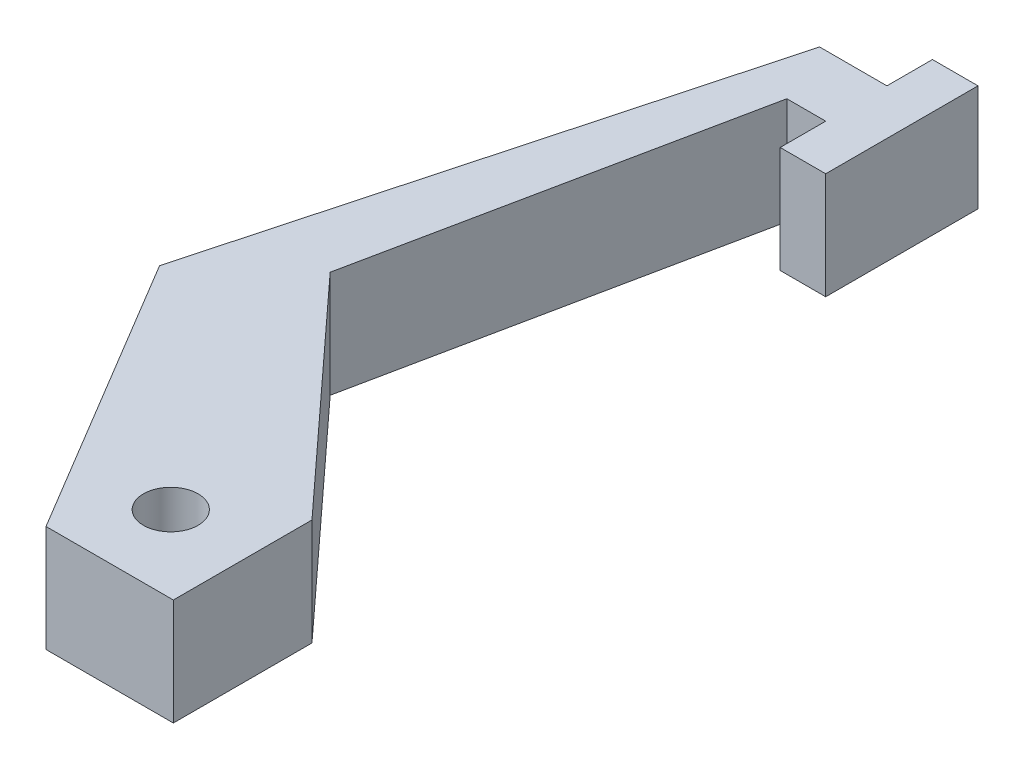
SolidWorks part; units mm, degrees
ref_plane "Front Plane" through (0, 0, 0) normal (0, 0, 1) x (1, 0, 0)
ref_plane "Top Plane" through (0, 0, 0) normal (0, 1, 0) x (1, 0, 0)
ref_plane "Right Plane" through (0, 0, 0) normal (1, 0, 0) x (0, 0, -1)
sketch "Sketch1" plane through (0, 0, 0) normal (0, 1, 0) x (1, 0, 0)
  line L13 (0, 0) -> (-13.9808, 0)
  line L14 (0, 0) -> (0, 15.2189)
  line L15 (0, 15.2189) -> (-22.5542, 39.772)
  line L16 (-22.5542, 39.772) -> (-13.9808, 81.3354)
  line L17 (-13.9808, 81.3354) -> (-9.7151, 81.3354)
  line L18 (-9.7151, 81.3354) -> (-9.7151, 76.3354)
  line L19 (-9.7151, 76.3354) -> (-4.7151, 76.3354)
  line L20 (-4.7151, 76.3354) -> (-4.7151, 93.0551)
  line L21 (-4.7151, 93.0551) -> (-9.7151, 93.0551)
  line L22 (-9.7151, 93.0551) -> (-9.7151, 88.0551)
  line L23 (-9.7151, 88.0551) -> (-17.1058, 88.0551)
  line L24 (-17.1058, 88.0551) -> (-32.5429, 31.0284)
  line L25 (-32.5429, 31.0284) -> (-13.9808, 0)
  circle A0 centre (-8.7368, 8.4549) radius 3
  point P12 (0, 0)
  point P14 (0, 0)
  point P15 (-8.7368, 8.4549)
  point P16 (0, 15.2189)
  point P17 (-13.9808, 0)
  point P18 (-30.8436, 47.8887)
  point P19 (-38.5545, 39.772)
  point P20 (-14.0801, 100.102)
  point P21 (-17.0875, 112.1316)
  point P22 (0, 0)
  point P23 (0, 0)
  point P24 (0, 0)
  point P27 (-27.7805, 44.9665)
  point P28 (-9.7151, 90.5551)
  point P29 (0, 0)
  point P31 (-15.4712, 85.5125)
  point P32 (-22.5542, 39.772)
  point P33 (-32.5429, 31.0284)
  point P34 (-17.1058, 88.0551)
  point P35 (-13.9808, 81.3354)
  point P36 (0, 0)
extrude "Boss-Extrude2" add sketch "Sketch1" along normal blind 11.7
